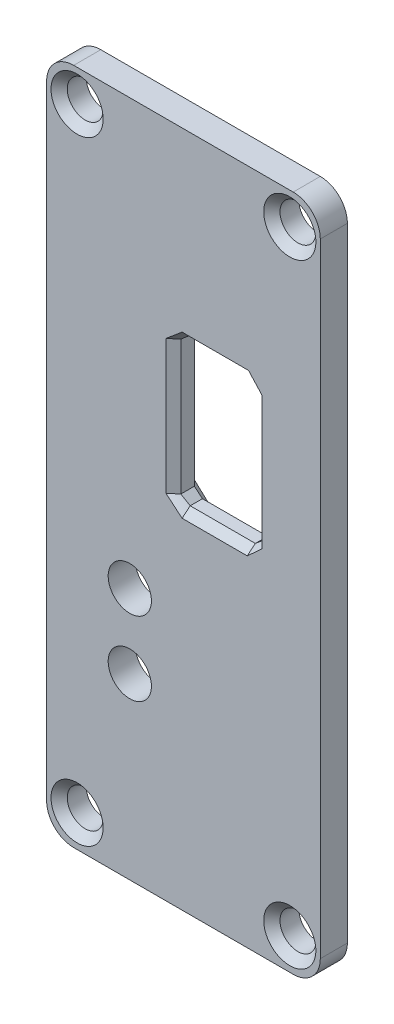
SolidWorks part; units mm, degrees
ref_plane "前视基准面" through (0, 0, 0) normal (0, 0, 1) x (1, 0, 0)
ref_plane "上视基准面" through (0, 0, 0) normal (0, 1, 0) x (1, 0, 0)
ref_plane "右视基准面" through (0, 0, 0) normal (1, 0, 0) x (0, 0, -1)
sketch "草图1" plane through (0, 0, 0) normal (0, 0, 1) x (1, 0, 0)
  line L0 (-16.5, 25) -> (3.7, 25)
  line L1 (-16.5, 25) -> (-16.5, -25)
  line L2 (-16.5, -25) -> (3.7, -25)
  line L3 (3.7, 25) -> (3.7, -25)
  line L4 (-6.495, 10.95) -> (-1.695, 10.95) construction
  line L5 (-7.095, 11.45) -> (-1.095, 11.45)
  line L6 (-7.095, 11.45) -> (-7.095, 0.55)
  line L7 (-7.095, 0.55) -> (-1.095, 0.55)
  line L8 (-1.095, 11.45) -> (-1.095, 0.55)
  line L9 (-1.695, 1.05) -> (-6.495, 1.05) construction
  line L10 (-1.595, 10.85) -> (-1.595, 1.15) construction
  line L11 (-6.595, 1.15) -> (-6.595, 10.85) construction
  circle A0 centre (-14.25, -22.65) radius 1.325
  circle A1 centre (-14.25, 22.65) radius 1.325
  circle A2 centre (1.45, 22.65) radius 1.325
  circle A3 centre (1.45, -22.65) radius 1.325
  circle A4 centre (-10.36, -6.365) radius 1.595
  circle A5 centre (-10.36, -11.8216) radius 1.595
  circle A6 centre (-14.25, 22.65) radius 1.325 construction
  arc A7 (-9.3041, -6.075) -> (-11.4159, -6.075) centre (-10.36, -6.365) ccw construction
  arc A8 (-9.3041, -11.5316) -> (-11.4159, -11.5316) centre (-10.36, -11.8216) ccw construction
  dimension "D11" = 0.5
  dimension "D12" = 0.5
  dimension "D1" = 2.35
  dimension "D2" = 2.25
  dimension "D3" = 50
  dimension "D4" = 20.2
  dimension "D5" = 45.3
  dimension "D6" = 15.7
  dimension "D7" = 0.5
  dimension "D8" = 0.5
  dimension "D9" = 0.5
  dimension "D10" = 0.5
extrude "凸台-拉伸1" add sketch "草图1" along normal blind 2
fillet "圆角1" radius 2 4 edges at (-16.5, 25, 1) (3.7, 25, 1) (3.7, -25, 1) (-16.5, -25, 1)
chamfer "倒角1" distance 0.6 angle 45 4 edges at (-12.925, 22.65, 2) (2.775, 22.65, 2) (2.775, -22.65, 2) (-12.925, -22.65, 2)
chamfer "倒角2" distance 0.5 angle 50 12 edges at (-4.095, 0.55, 2) (-4.095, 0.55, 0) (-4.095, 11.45, 2) (-1.095, 11.45, 1) (-1.095, 6, 2) (-1.095, 0.55, 1) (-1.095, 6, 0) (-4.095, 11.45, 0) (-7.095, 0.55, 1) (-7.095, 6, 2) (-7.095, 11.45, 1) (-7.095, 6, 0)
